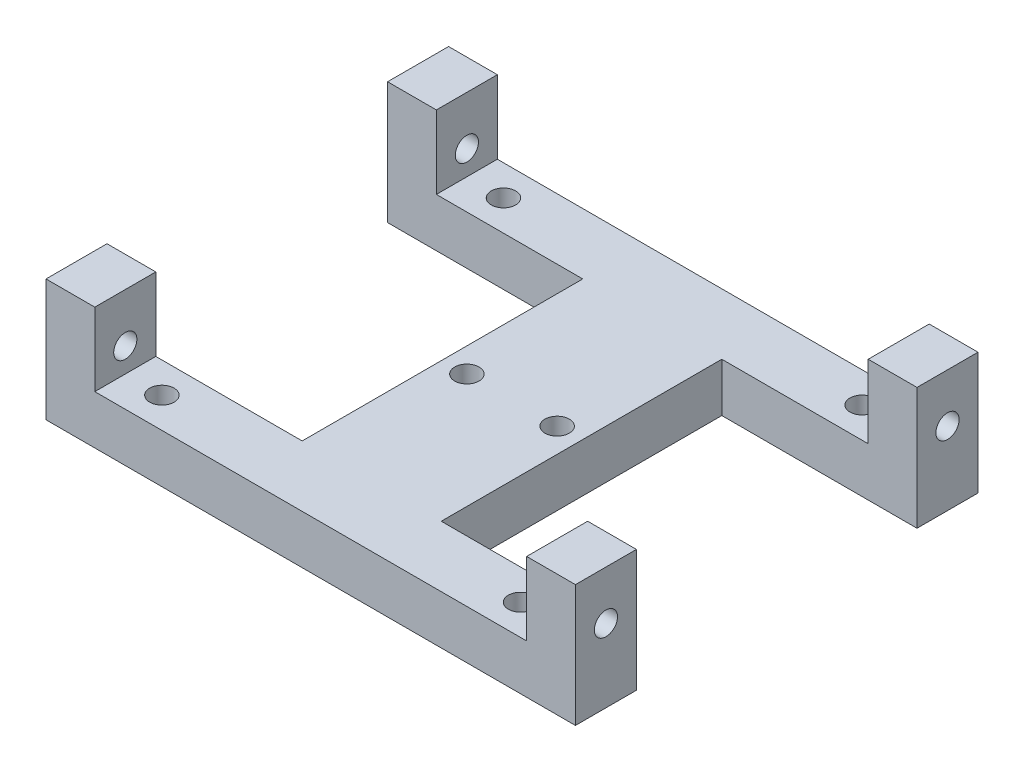
SolidWorks part; units mm, degrees
ref_plane "前视基准面" through (0, 0, 0) normal (0, 0, 1) x (1, 0, 0)
ref_plane "上视基准面" through (0, 0, 0) normal (0, 1, 0) x (1, 0, 0)
ref_plane "右视基准面" through (0, 0, 0) normal (1, 0, 0) x (0, 0, -1)
other "Configuration Table"
sketch "草图1" plane through (0, 0, 0) normal (0, 1, 0) x (1, 0, 0)
  line L0 (0, 0) -> (0, -5)
  line L1 (0, -5) -> (20, -5)
  line L2 (0, 0) -> (16, 0)
  line L9 (16, 0) -> (16, 23)
  line L11 (20, 28) -> (0, 28)
  line L12 (16, 23) -> (0, 23)
  line L13 (0, 23) -> (0, 28)
  line L14 (43.4, 23) -> (43.4, 28)
  line L15 (21.7, 11.7776) -> (21.7, 13.9504) construction
  line L16 (27.4, 23) -> (43.4, 23)
  line L17 (23.4, 28) -> (43.4, 28)
  line L19 (27.4, 0) -> (27.4, 23)
  line L21 (43.4, 0) -> (27.4, 0)
  line L22 (43.4, -5) -> (23.4, -5)
  line L23 (43.4, 0) -> (43.4, -5)
  line L24 (20, -5) -> (23.4, -5)
  line L25 (20, 28) -> (23.4, 28)
extrude "凸台-拉伸1" add sketch "草图1" along normal blind 4
sketch "草图2" plane through (0, 4, 0) normal (0, 1, 0) x (1, 0, 0)
  line L0 (0, 0) -> (4, 0)
  line L1 (16, 0) -> (0, 0) construction
  line L2 (4, 0) -> (4, -5)
  line L3 (0, -5) -> (43.4, -5) construction
  line L4 (4, -5) -> (0, -5)
  line L5 (0, -5) -> (0, 0)
  line L6 (4, 28) -> (4, 23)
  line L7 (0, 28) -> (4, 28)
  line L8 (0, 23) -> (0, 28)
  line L9 (4, 23) -> (0, 23)
  line L14 (39.4, -5) -> (43.4, -5)
  line L15 (39.4, 0) -> (39.4, -5)
  line L16 (43.4, 0) -> (39.4, 0)
  line L17 (43.4, -5) -> (43.4, 0)
  line L18 (43.4, 28) -> (39.4, 28)
  line L19 (43.4, 23) -> (43.4, 28)
  line L20 (39.4, 23) -> (43.4, 23)
  line L21 (39.4, 28) -> (39.4, 23)
extrude "凸台-拉伸2" add sketch "草图2" along normal blind 6
sketch "草图3" plane through (0, 0, 0) normal (-1, 0, 0) x (0, 0, 1)
  circle A0 centre (2.5, 6) radius 0.95
  circle A1 centre (-25.5, 6) radius 0.95
extrude "切除-拉伸1" cut sketch "草图3" against normal through all
sketch "草图4" plane through (0, 4, 0) normal (0, 1, 0) x (1, 0, 0)
  circle A0 centre (7, -2.5) radius 1
  circle A1 centre (7, 25.5) radius 1
  circle A2 centre (18, 11.5) radius 1
  circle A3 centre (36.4, -2.5) radius 1
  circle A4 centre (36.4, 25.5) radius 1
  circle A5 centre (25.4, 11.5) radius 1
extrude "切除-拉伸2" cut sketch "草图4" against normal through all
